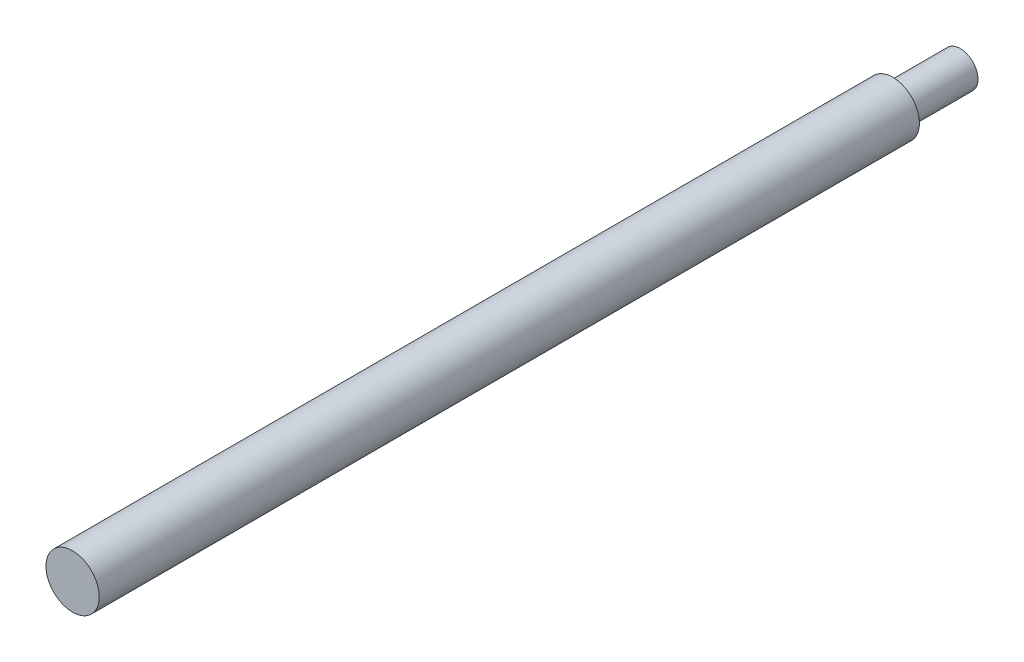
SolidWorks part; units mm, degrees
ref_plane "Ön Düzlem" through (0, 0, 0) normal (0, 0, 1) x (1, 0, 0)
ref_plane "Üst Düzlem" through (0, 0, 0) normal (0, 1, 0) x (1, 0, 0)
ref_plane "Sağ Düzlem" through (0, 0, 0) normal (1, 0, 0) x (0, 0, -1)
sketch "Sketch1" plane through (0, 0, 0) normal (0, 0, 1) x (1, 0, 0)
  circle A0 centre (0, 0) radius 7.5
  dimension "D1" = 15
extrude "Boss-Extrude1" add sketch "Sketch1" along normal blind 250
sketch "Sketch2" plane through (0, 0, 0) normal (0, 0, 1) x (1, 0, 0)
  circle A0 centre (0, 0) radius 5
  circle A1 centre (0, 0) radius 8.3227
  dimension "D1" = 10
extrude "Cut-Extrude1" cut sketch "Sketch2" along normal blind 19
